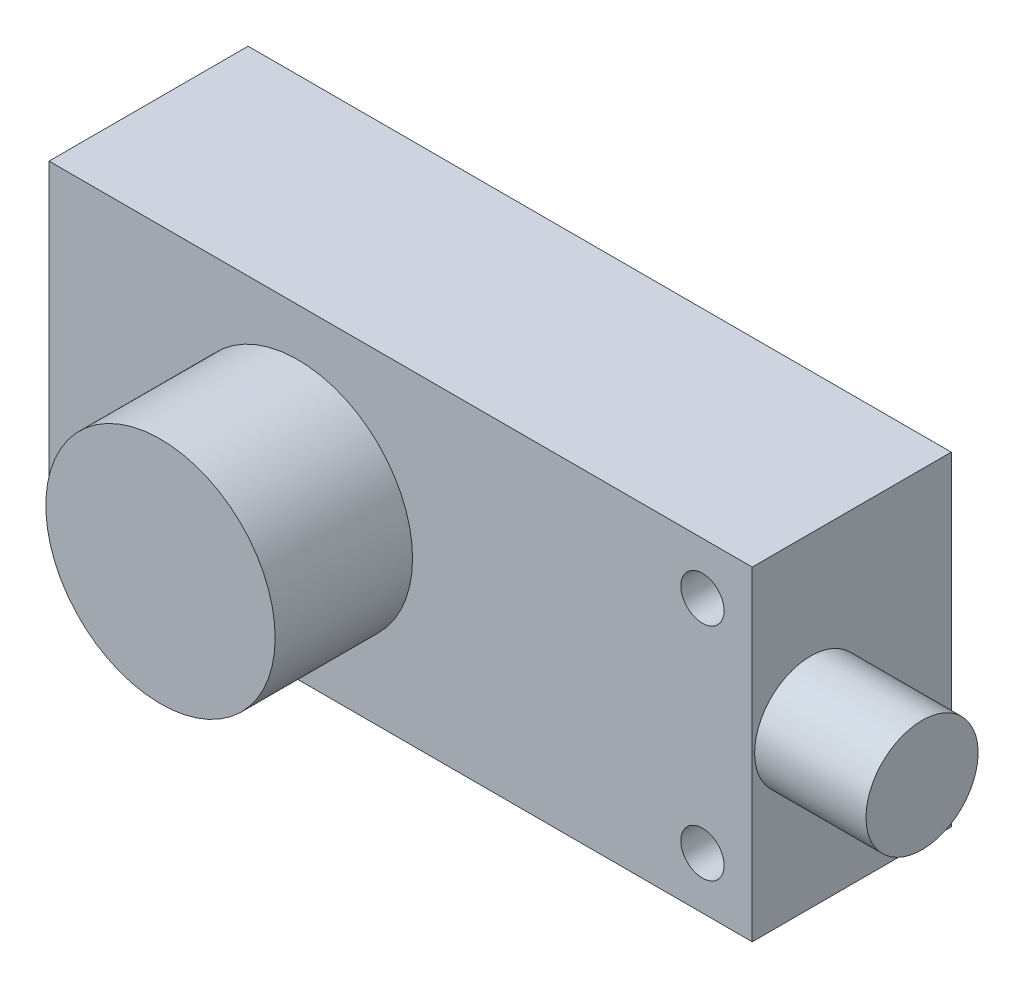
SolidWorks part; units mm, degrees
ref_plane "Plan de face" through (0, 0, 0) normal (0, 0, 1) x (1, 0, 0)
ref_plane "Plan de dessus" through (0, 0, 0) normal (0, 1, 0) x (1, 0, 0)
ref_plane "Plan de droite" through (0, 0, 0) normal (1, 0, 0) x (0, 0, -1)
sketch "Esquisse1" plane through (0, 0, 0) normal (0, 0, 1) x (1, 0, 0)
  line L1 (32.5, -15) -> (-32.5, -15)
  line L2 (32.5, -15) -> (32.5, 15)
  line L3 (32.5, 15) -> (-32.5, 15)
  line L4 (-32.5, -15) -> (-32.5, 15)
  line L5 (32.5, -15) -> (-32.5, 15) construction
  line L6 (32.5, 15) -> (-32.5, -15) construction
  point P0 (0, 0)
extrude "Boss.-Extru.1" add sketch "Esquisse1" along normal blind 18.4
sketch "Esquisse2" plane through (0, 0, 18.4) normal (0, 0, 1) x (1, 0, 0)
  circle A0 centre (-9.5, 0) radius 10.6
extrude "Boss.-Extru.2" add sketch "Esquisse2" along normal blind 12.7
sketch "Esquisse4" plane through (0, 0, 18.4) normal (0, 0, 1) x (1, 0, 0)
  circle A0 centre (27.9, -10.2) radius 2
extrude "Enlèv. mat.-Extru.2" cut sketch "Esquisse4" against normal through all
sketch "Esquisse5" plane through (0, 0, 18.4) normal (0, 0, 1) x (1, 0, 0)
  circle A0 centre (27.9, 10.2) radius 2
extrude "Enlèv. mat.-Extru.3" cut sketch "Esquisse5" against normal through all
sketch "Esquisse6" plane through (32.5, 0, 0) normal (1, 0, 0) x (0, 0, -1)
  circle A0 centre (-13, 0) radius 5.18
extrude "Boss.-Extru.3" add sketch "Esquisse6" along normal blind 10.3
